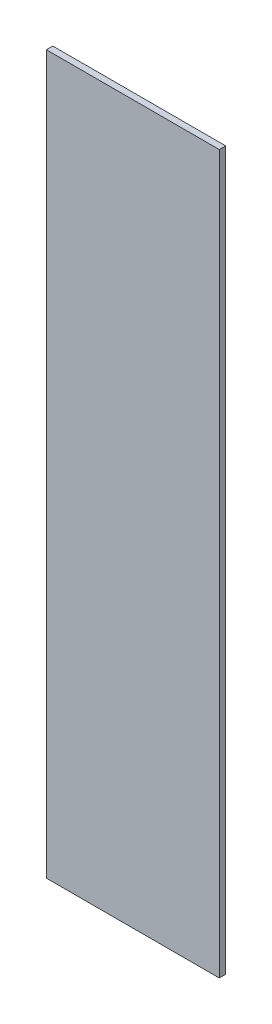
SolidWorks part; units mm, degrees
ref_plane "Front" through (0, 0, 0) normal (0, 0, 1) x (1, 0, 0)
ref_plane "Top" through (0, 0, 0) normal (0, 1, 0) x (1, 0, 0)
ref_plane "Right" through (0, 0, 0) normal (1, 0, 0) x (0, 0, -1)
sketch "Sketch1" plane through (0, 0, 0) normal (0, 0, 1) x (1, 0, 0)
  line L5 (-171.45, -711.2) -> (171.45, -711.2)
  line L6 (-171.45, -711.2) -> (-171.45, 711.2)
  line L7 (-171.45, 711.2) -> (171.45, 711.2)
  line L8 (171.45, -711.2) -> (171.45, 711.2)
  line L9 (-171.45, -711.2) -> (171.45, 711.2) construction
  line L10 (-171.45, 711.2) -> (171.45, -711.2) construction
  point P4 (0, 0)
  dimension "D1" = 342.9
  dimension "D2" = 1422.4
extrude "Boss-Extrude1" add sketch "Sketch1" along normal blind 12.7
